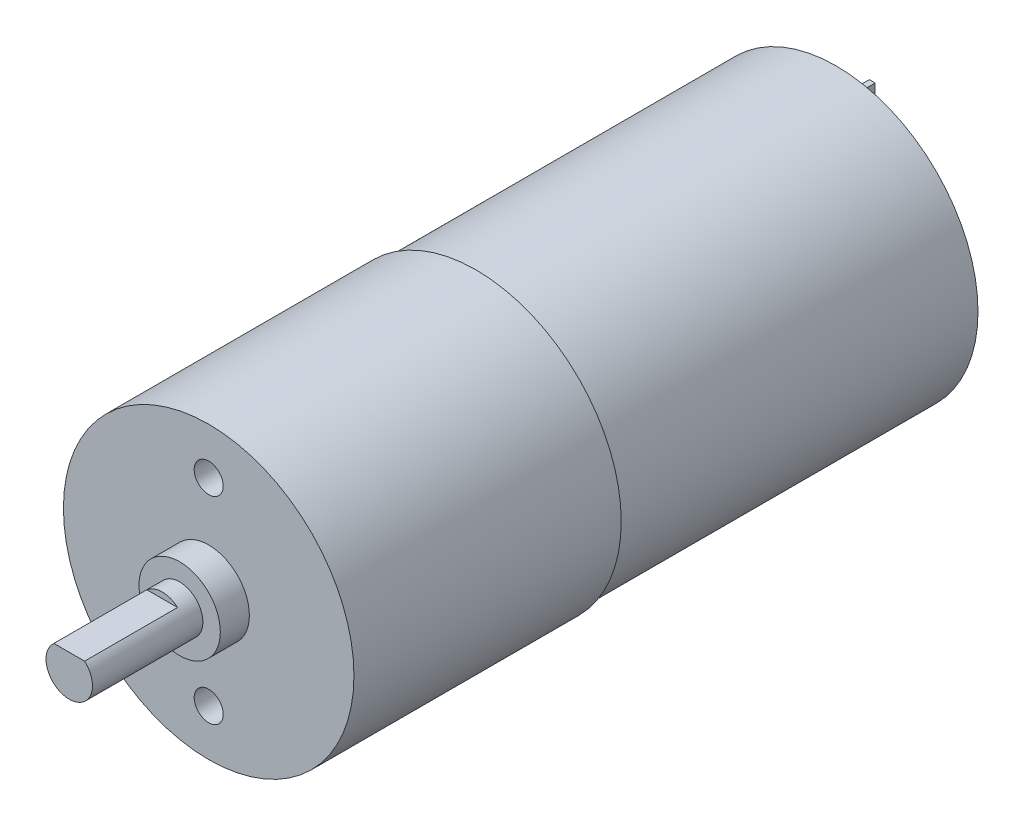
SolidWorks part; units mm, degrees
ref_plane "Front Plane" through (0, 0, 0) normal (0, 0, 1) x (1, 0, 0)
ref_plane "Top Plane" through (0, 0, 0) normal (0, 1, 0) x (1, 0, 0)
ref_plane "Right Plane" through (0, 0, 0) normal (1, 0, 0) x (0, 0, -1)
sketch "Sketch1" plane through (0, 0, 0) normal (0, 0, 1) x (1, 0, 0)
  circle A0 centre (0, 0) radius 12.5
  dimension "D1" = 25
extrude "Boss-Extrude1" add sketch "Sketch1" against normal blind 23
sketch "Sketch2" plane through (0, 0, 0) normal (0, 0, 1) x (1, 0, 0)
  circle A0 centre (0, 0) radius 3.5
  dimension "D1" = 7
extrude "Boss-Extrude2" add sketch "Sketch2" along normal blind 2.5
sketch "Sketch3" plane through (0, 0, 2.5) normal (0, 0, 1) x (1, 0, 0)
  circle A0 centre (0, 0) radius 2
  dimension "D1" = 4
extrude "Boss-Extrude4" add sketch "Sketch3" along normal offset from surface (9.5 mm away) 12 up to face at (12.5, 0, 0) offset beyond the face yes
sketch "Sketch4" plane through (0, 0, 12) normal (0, 0, 1) x (1, 0, 0)
  line L1 (-1.3229, 1.5) -> (1.3229, 1.5)
  line L2 (-1.3229, 1.5) -> (-1.3229, 2)
  line L3 (-1.3229, 2) -> (1.3229, 2)
  line L4 (1.3229, 1.5) -> (1.3229, 2)
  circle A0 centre (0, 0) radius 2 construction
  circle A1 centre (0, 0) radius 2 construction
  dimension "D1" = 3.5
extrude "Cut-Extrude1" cut sketch "Sketch4" against normal blind 8
sketch "Sketch5" plane through (0, 0, -23) normal (0, 0, -1) x (-1, 0, 0)
  circle A0 centre (0, 0) radius 12.2
  dimension "D1" = 24.4
extrude "Boss-Extrude5" add sketch "Sketch5" along normal blind 31
sketch "Sketch6" plane through (0, 0, -54) normal (0, 0, -1) x (-1, 0, 0)
  circle A0 centre (0, 0) radius 3.2
  dimension "D1" = 6.4
extrude "Boss-Extrude6" add sketch "Sketch6" along normal blind 1.4
sketch "Sketch7" plane through (0, 0, -54) normal (0, 0, -1) x (-1, 0, 0)
  line L0 (0, -7.5) -> (0, 7.5) construction
  line L1 (-0.25, 9.5) -> (0.25, 9.5)
  line L2 (-0.25, 9.5) -> (-0.25, 7.5)
  line L3 (-0.25, 7.5) -> (0.25, 7.5)
  line L4 (0.25, 9.5) -> (0.25, 7.5)
  line L5 (-0.25, -7.5) -> (0.25, -7.5)
  line L6 (-0.25, -7.5) -> (-0.25, -9.5)
  line L7 (-0.25, -9.5) -> (0.25, -9.5)
  line L8 (0.25, -7.5) -> (0.25, -9.5)
  dimension "D1" = 0.5
  dimension "D2" = 2
  dimension "D3" = 15
extrude "Boss-Extrude7" add sketch "Sketch7" along normal blind 3.1
hole_wizard "M3 Tapped Hole1" positions "Sketch9" profile "Sketch8" tap size "M3" standard "ISO"
sketch "Sketch9" plane through (0, 0, 0) normal (0, 0, 1) x (1, 0, 0)
  line L0 (0, 8.5) -> (0, -8.5) construction
  point P0 (0, 8.5)
  point P2 (0, -8.5)
  dimension "D1" = 17
sketch "Sketch8" plane through (0, 8.5, 0) normal (1, 0, 0) x (0, -1, 0)
  line L0 (0, 0) -> (0, 9.2511)
  line L1 (0, 9.2511) -> (1.25, 8.5)
  line L2 (1.25, 8.5) -> (1.25, 0)
  line L5 (1.25, 0) -> (0, 0)
  line L10 (0, 9.2511) -> (-1.25, 8.5) construction
  line L11 (0, -6.35) -> (0, 107.95) construction
  dimension "Tap Drill Dia." = 2.5
  dimension "Tap Drill Depth" = 8.5
  dimension "Drill Angle" = 118
cosmetic thread "Hole Thread1" parameters "D1"=6, "D2"=3
cosmetic thread "Hole Thread2" parameters "D1"=6, "D2"=3
